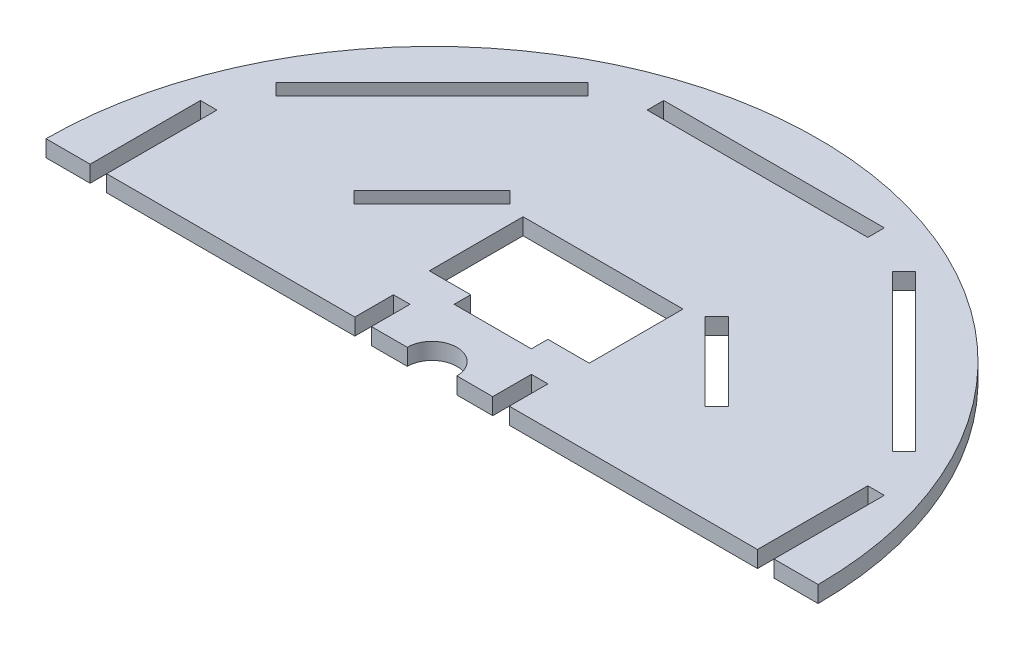
SolidWorks part; units mm, degrees
ref_plane "Alzado" through (0, 0, 0) normal (0, 0, 1) x (1, 0, 0)
ref_plane "Planta" through (0, 0, 0) normal (0, 1, 0) x (1, 0, 0)
ref_plane "Vista lateral" through (0, 0, 0) normal (1, 0, 0) x (0, 0, -1)
sketch "Croquis1" plane through (0, 0, 0) normal (0, 1, 0) x (1, 0, 0)
  line L0 (0, 11) -> (7, 11)
  line L1 (7, 11) -> (7, 14)
  line L2 (24.7487, 24.7487) -> (31.8198, 17.6777)
  line L3 (-7, 14) -> (-7, 11)
  line L4 (-7, 11) -> (0, 11)
  line L5 (11, 0) -> (11, 7)
  line L6 (11, 7) -> (14, 7)
  line L7 (-70, 0) -> (-62, 0)
  line L8 (-59, 0) -> (-17, 0)
  line L9 (-11, 0) -> (-4.5, 0)
  line L10 (-3.182, 3.182) -> (-24.7487, 24.7487) construction
  line L11 (-24.7487, 24.7487) -> (-17.6777, 31.8198)
  line L12 (-17.6777, 31.8198) -> (-19.799, 33.9411)
  line L13 (4.5, 0) -> (11, 0)
  line L14 (17, 0) -> (59, 0)
  line L15 (-11, 0) -> (-11, 7)
  line L16 (-11, 7) -> (-14, 7)
  line L17 (62, 0) -> (70, 0)
  line L18 (-14, 7) -> (-14, 0)
  line L19 (-14, 0) -> (-17, 0)
  line L20 (14, 7) -> (14, 0)
  line L21 (14, 0) -> (17, 0)
  line L23 (-19.799, 33.9411) -> (-33.9411, 19.799)
  line L24 (-24.7487, 24.7487) -> (-31.8198, 17.6777)
  line L25 (-31.8198, 17.6777) -> (-33.9411, 19.799)
  line L26 (7, 14) -> (14.5, 14)
  line L27 (14.5, 14) -> (14.5, 31)
  line L28 (14.5, 31) -> (-14.5, 31)
  line L29 (-14.5, 31) -> (-14.5, 14)
  line L30 (-14.5, 14) -> (-7, 14)
  line L31 (31.8198, 17.6777) -> (33.9411, 19.799)
  line L32 (33.9411, 19.799) -> (19.799, 33.9411)
  line L33 (17.6777, 31.8198) -> (19.799, 33.9411)
  line L34 (24.7487, 24.7487) -> (17.6777, 31.8198)
  line L41 (0, 4.5) -> (0, 62) construction
  line L42 (0, 62) -> (20, 62)
  line L43 (20, 62) -> (20, 59)
  line L44 (20, 59) -> (-20, 59)
  line L45 (-20, 59) -> (-20, 62)
  line L46 (-20, 62) -> (0, 62)
  line L47 (55.8614, 27.5772) -> (27.5772, 55.8614)
  line L48 (27.5772, 55.8614) -> (29.6985, 57.9828)
  line L49 (29.6985, 57.9828) -> (43.8406, 43.8406)
  line L50 (43.8406, 43.8406) -> (57.9828, 29.6985)
  line L51 (57.9828, 29.6985) -> (55.8614, 27.5772)
  line L52 (59, 0) -> (59, 20)
  line L53 (59, 20) -> (62, 20)
  line L54 (62, 20) -> (62, 0)
  line L72 (-59, 20) -> (-59, 0)
  line L75 (-62, 0) -> (-62, 20)
  line L76 (-62, 20) -> (-59, 20)
  line L77 (-27.5772, 55.8614) -> (-55.8614, 27.5772)
  line L78 (-55.8614, 27.5772) -> (-57.9828, 29.6985)
  line L79 (-57.9828, 29.6985) -> (-43.8406, 43.8406)
  line L80 (-43.8406, 43.8406) -> (-29.6985, 57.9828)
  line L81 (-29.6985, 57.9828) -> (-27.5772, 55.8614)
  line L103 (62, 0) -> (62, -20) [skipped]
  line L104 (24.7487, -24.7487) -> (17.6777, -31.8198) [skipped]
  line L105 (19.799, -33.9411) -> (33.9411, -19.799) [skipped]
  line L106 (24.7487, -24.7487) -> (31.8198, -17.6777) [skipped]
  line L107 (17.6777, -31.8198) -> (19.799, -33.9411) [skipped]
  line L108 (31.8198, -17.6777) -> (33.9411, -19.799) [skipped]
  line L109 (-62, -20) -> (-62, 0) [skipped]
  line L110 (-24.7487, -24.7487) -> (-31.8198, -17.6777) [skipped]
  line L111 (62, -20) -> (59, -20) [skipped]
  line L112 (27.5772, -55.8614) -> (55.8614, -27.5772) [skipped]
  line L113 (55.8614, -27.5772) -> (57.9828, -29.6985) [skipped]
  line L114 (57.9828, -29.6985) -> (43.8406, -43.8406) [skipped]
  line L115 (43.8406, -43.8406) -> (29.6985, -57.9828) [skipped]
  line L116 (29.6985, -57.9828) -> (27.5772, -55.8614) [skipped]
  line L117 (-20, -59) -> (20, -59) [skipped]
  line L118 (20, -59) -> (20, -62) [skipped]
  line L119 (20, -62) -> (0, -62) [skipped]
  line L120 (0, -62) -> (-20, -62) [skipped]
  line L121 (-20, -62) -> (-20, -59) [skipped]
  line L122 (-55.8614, -27.5772) -> (-27.5772, -55.8614) [skipped]
  line L123 (-27.5772, -55.8614) -> (-29.6985, -57.9828) [skipped]
  line L124 (-29.6985, -57.9828) -> (-43.8406, -43.8406) [skipped]
  line L125 (-43.8406, -43.8406) -> (-57.9828, -29.6985) [skipped]
  line L126 (-57.9828, -29.6985) -> (-55.8614, -27.5772) [skipped]
  line L127 (-59, -20) -> (-62, -20) [skipped]
  line L128 (-31.8198, -17.6777) -> (-33.9411, -19.799) [skipped]
  line L129 (-33.9411, -19.799) -> (-19.799, -33.9411) [skipped]
  line L130 (-17.6777, -31.8198) -> (-19.799, -33.9411) [skipped]
  line L131 (-24.7487, -24.7487) -> (-17.6777, -31.8198) [skipped]
  arc A0 (4.5, 0) -> (-4.5, 0) centre (0, 0) ccw
  arc A2 (70, 0) -> (-70, 0) centre (0, 0) ccw
  point P47 (0, 0)
  point P88 (0, 0)
  point P93 (0, 0)
  dimension "D4" = 7
  dimension "D5" = 3
  dimension "D6" = 14
  dimension "D8" = 3
  dimension "D9" = 10
  dimension "D10" = 3
  dimension "D11" = 20
  dimension "D12" = 10
  dimension "D15" = 20
  dimension "D16" = 3
  dimension "D17" = 40
  dimension "D19" = 17
  dimension "D13" = 4
  dimension "D20" = 29
  dimension "D21" = 3
  dimension "D18" = 8
extrude "Saliente-Extruir1" add sketch "Croquis1" along normal blind 3
